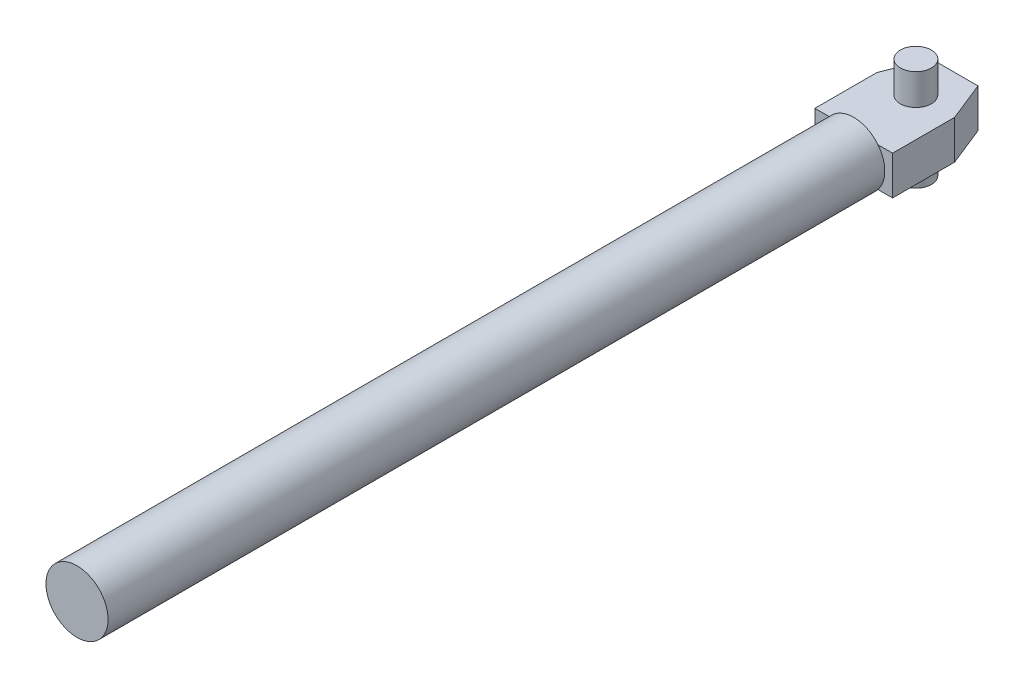
SolidWorks part; units mm, degrees
ref_plane "Front Plane" through (0, 0, 0) normal (0, 0, 1) x (1, 0, 0)
ref_plane "Top Plane" through (0, 0, 0) normal (0, 1, 0) x (1, 0, 0)
ref_plane "Right Plane" through (0, 0, 0) normal (1, 0, 0) x (0, 0, -1)
sketch "Sketch1" plane through (0, 0, 0) normal (0, 0, 1) x (1, 0, 0)
  circle A0 centre (0, 0) radius 20
  dimension "D1" = 40
extrude "Boss-Extrude1" add sketch "Sketch1" along normal blind 500
sketch "Sketch2" plane through (0, 0, 0) normal (0, 1, 0) x (1, 0, 0)
  line L0 (-25, 40) -> (-15, 65)
  line L1 (-25, 0) -> (25, 0)
  line L2 (-25, 0) -> (-25, 40)
  line L3 (-15, 65) -> (15, 65)
  line L4 (25, 0) -> (25, 40)
  line L5 (15, 65) -> (25, 40)
  point P1 (25, 65)
  point P2 (-25, 65)
  dimension "D1" = 50
  dimension "D2" = 65
  dimension "D3" = 25
  dimension "D4" = 10
  dimension "D5" = 10
  dimension "D6" = 25
extrude "Boss-Extrude6" add sketch "Sketch2" along normal mid plane 25
sketch "Sketch6" plane through (0, 12.5, 0) normal (0, 1, 0) x (1, 0, 0)
  line L0 (-15.6125, 0) -> (15.6125, 0) construction
  circle A0 centre (0, 40) radius 10
  point P2 (0, 0)
  dimension "D1" = 20
  dimension "D2" = 40
extrude "Boss-Extrude7" add sketch "Sketch6" along normal blind 20 and the other way blind 45
